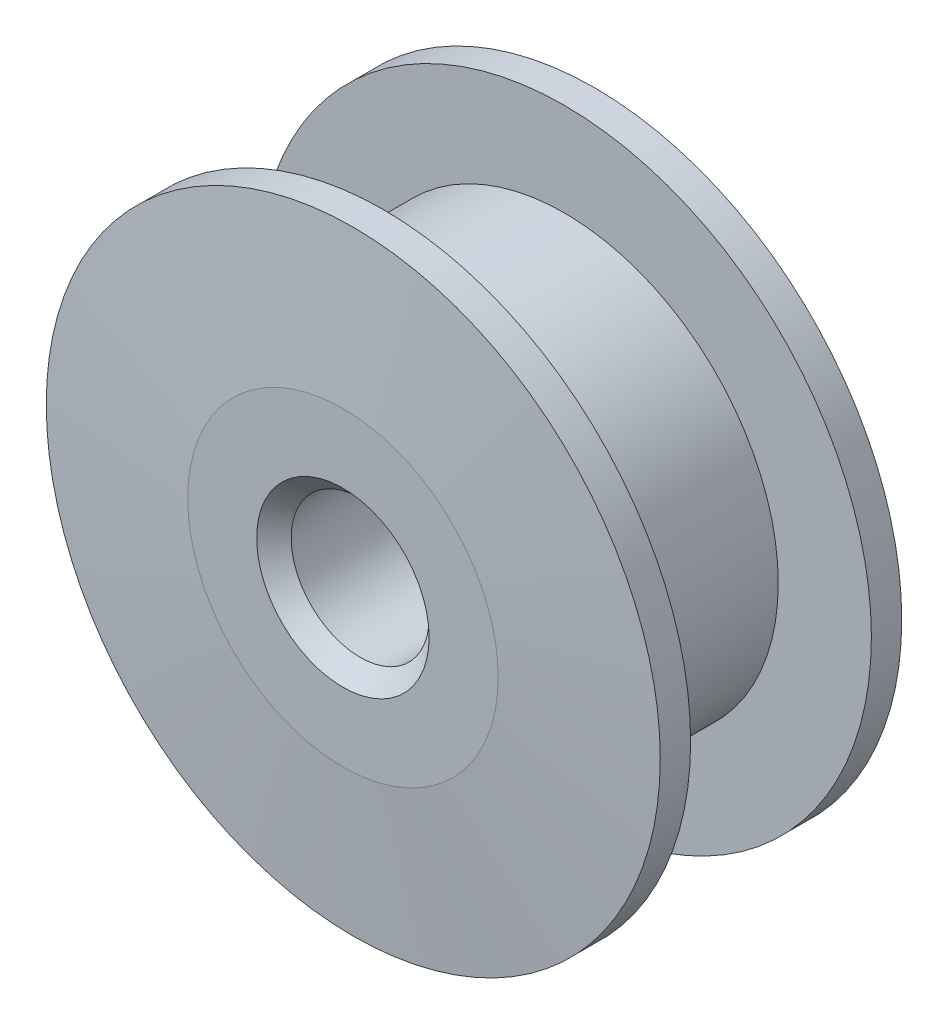
SolidWorks part; units mm, degrees
material "7075-T6，板材(SS)"
ref_plane "前视基准面" through (0, 0, 0) normal (0, 0, 1) x (1, 0, 0)
ref_plane "上视基准面" through (0, 0, 0) normal (0, 1, 0) x (1, 0, 0)
ref_plane "右视基准面" through (0, 0, 0) normal (1, 0, 0) x (0, 0, -1)
sketch "草图1" plane through (0, 0, 0) normal (0, 0, 1) x (1, 0, 0)
  circle A0 centre (0, 0) radius 4.45
  dimension "D1" = 8.9
extrude "拉伸1" add sketch "草图1" along normal mid plane 3.8
sketch "草图2" plane through (0, 0, 0) normal (0, 0, 1) x (1, 0, 0)
  circle A0 centre (0, 0) radius 4.45 construction
  circle A1 centre (0, 0) radius 4.45
  circle A2 centre (0, 0) radius 3.1
  dimension "D1" = 6.2
extrude "拉伸2" cut sketch "草图2" against normal mid plane 2.62
sketch "草图3" plane through (0, 0, 1.9) normal (0, 0, 1) x (1, 0, 0)
  circle A0 centre (0, 0) radius 1
  dimension "D1" = 2
extrude "拉伸3" cut sketch "草图3" against normal up to surface (3.8 mm away) up to face at (4.45, 0, -1.9)
chamfer "倒角1" distance 0.25 angle 45 2 edges at (1, 0, -1.9) (1, 0, 1.9)
chamfer "倒角2" distance 2 distance2 0.15 1 edges at (4.45, 0, -1.9)
chamfer "倒角3" distance 0.15 distance2 2.2 1 edges at (4.45, 0, 1.9)
